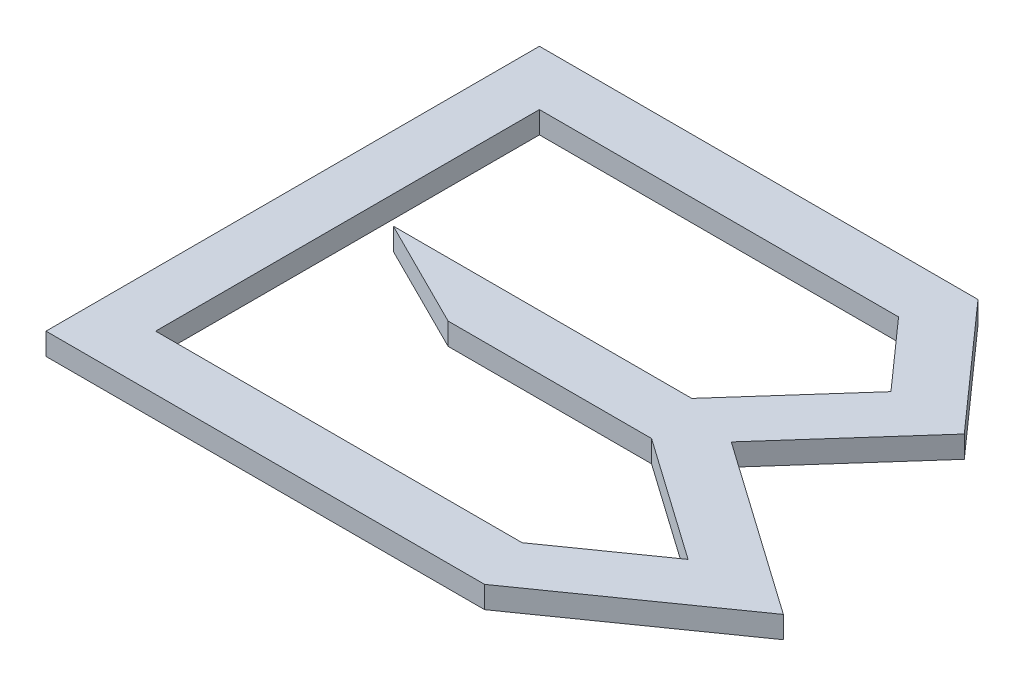
SolidWorks part; units mm, degrees
ref_plane "Front Plane" through (0, 0, 0) normal (0, 0, 1) x (1, 0, 0)
ref_plane "Top Plane" through (0, 0, 0) normal (0, 1, 0) x (1, 0, 0)
ref_plane "Right Plane" through (0, 0, 0) normal (1, 0, 0) x (0, 0, -1)
sketch "Sketch2" plane through (0, 0, 0) normal (0, 1, 0) x (1, 0, 0)
  line L0 (17.5, 22.5) -> (22.5, 22.5)
  line L1 (-17.5, 22.5) -> (17.5, 22.5)
  line L2 (-17.5, 22.5) -> (-17.5, -22.5)
  line L3 (-17.5, -22.5) -> (17.5, -22.5)
  line L5 (17.5, -22.5) -> (22.5, -22.5)
  line L6 (17.5, 17.5) -> (20.2547, 17.5)
  line L7 (20.2547, 17.5) -> (25.8102, 11.25)
  line L9 (25.8102, 11.25) -> (17.262, 1.6332)
  line L10 (18.5953, -3.3668) -> (29.807, -11.25)
  line L11 (29.807, -11.25) -> (20.9181, -17.5)
  line L12 (17.5, -17.5) -> (20.9181, -17.5)
  line L13 (-12.5, -17.5) -> (17.5, -17.5)
  line L14 (22.5, 22.5) -> (32.5, 11.25)
  line L15 (32.5, 11.25) -> (22.5, 0)
  line L16 (-12.5, 17.5) -> (-12.5, -17.5)
  line L17 (-12.5, 17.5) -> (17.5, 17.5)
  line L18 (22.5, 0) -> (38.5, -11.25)
  line L19 (38.5, -11.25) -> (22.5, -22.5)
  line L20 (15.0398, 1.6332) -> (17.262, 1.6332)
  line L21 (15.0398, -3.3668) -> (18.5953, -3.3668)
  line L22 (25.8102, 11.25) -> (15.0398, -0.8668) construction
  line L23 (15.0398, 1.6332) -> (-9.9602, 1.6332)
  line L24 (15.0398, -3.3668) -> (0.0398, -3.3668)
  line L25 (-9.9602, 1.6332) -> (0.0398, -3.3668)
  line L26 (15.0398, -0.8668) -> (29.807, -11.25) construction
  point P0 (0, 0)
  dimension "D1" = 5
extrude "Boss-Extrude1" add sketch "Sketch2" along normal blind 2
